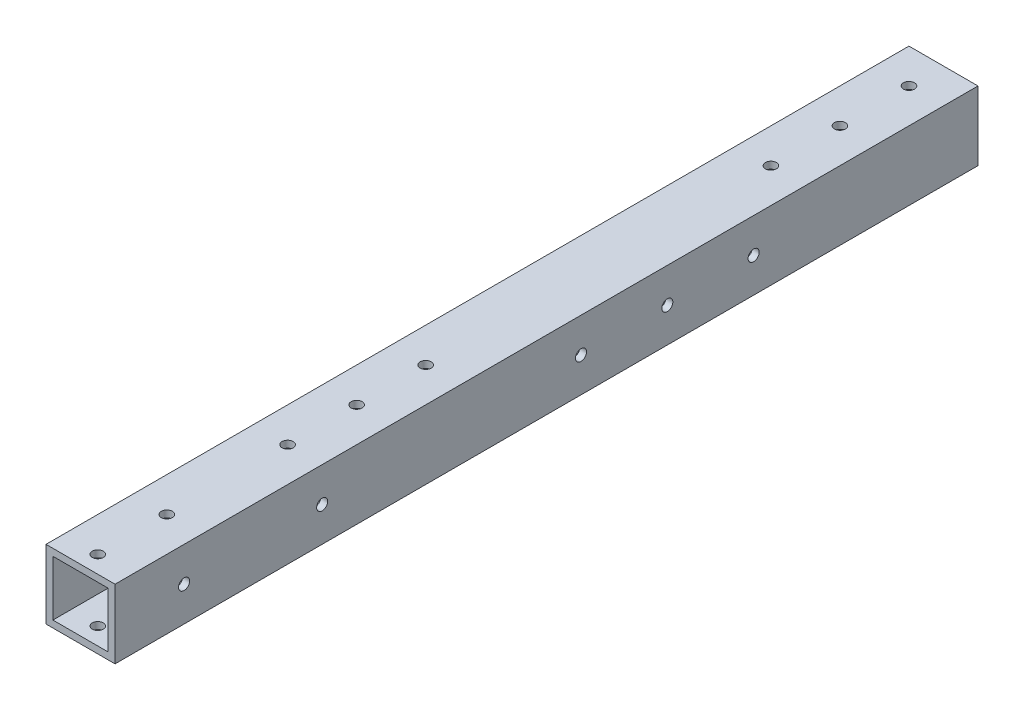
SolidWorks part; units mm, degrees
material "6061 合金"
ref_plane "前视基准面" through (0, 0, 0) normal (0, 0, 1) x (1, 0, 0)
ref_plane "上视基准面" through (0, 0, 0) normal (0, 1, 0) x (1, 0, 0)
ref_plane "右视基准面" through (0, 0, 0) normal (1, 0, 0) x (0, 0, -1)
other "Configuration Table"
sketch "草图1" plane through (0, 0, 0) normal (0, 0, 1) x (1, 0, 0)
  line L1 (0, 0) -> (20, 0)
  line L2 (0, 0) -> (0, 20)
  line L3 (0, 20) -> (20, 20)
  line L4 (20, 0) -> (20, 20)
  dimension "D1" = 20
  dimension "D2" = 20
extrude "拉伸-薄壁1" add sketch "草图1" along normal blind 250 thin thin type one direction reverse wall 2
sketch "草图2" plane through (0, 0, 0) normal (0, -1, 0) x (1, 0, 0)
  line L0 (10, 0) -> (10, 48.774) construction
  line L1 (0, 0) -> (20, 0) construction
  circle A0 centre (10, 10) radius 1.6
  circle A1 centre (10, 30) radius 1.6
  circle A2 centre (10, 50) radius 1.6
  dimension "D1" = 3.2
  dimension "D2" = 10
  dimension "D3" = 20
  dimension "D4" = 20
extrude "切除-拉伸1" cut sketch "草图2" against normal through all
sketch "草图3" plane through (0, 20, 0) normal (0, 1, 0) x (1, 0, 0)
  line L0 (10, -250) -> (10, -150) construction
  line L1 (20, -250) -> (0, -250) construction
  circle A0 centre (10, -150) radius 1.6
  circle A1 centre (10, -170) radius 1.6
  circle A2 centre (10, -190) radius 1.6
  circle A3 centre (10, -245) radius 1.6
  circle A4 centre (10, -225) radius 1.6
  dimension "D2" = 3.2
  dimension "D3" = 20
  dimension "D4" = 20
  dimension "D5" = 5
  dimension "D6" = 20
  dimension "D1" = 100
extrude "切除-拉伸2" cut sketch "草图3" against normal through all
sketch "草图4" plane through (20, 0, 0) normal (1, 0, 0) x (0, 0, -1)
  line L0 (-250, 10) -> (-230, 10) construction
  line L1 (-250, 0) -> (-250, 20) construction
  circle A0 centre (-230, 10) radius 1.6
  circle A1 centre (-190, 10) radius 1.6
  point P7 (0, 0)
  dimension "D1" = 3.2
  dimension "D3" = 40
  dimension "D2" = 20
extrude "切除-拉伸3" cut sketch "草图4" against normal through all
sketch "草图5" plane through (20, 0, 0) normal (1, 0, 0) x (0, 0, -1)
  line L0 (0, 10) -> (-114.4239, 10) construction
  line L1 (0, 0) -> (0, 20) construction
  circle A0 centre (-90, 10) radius 1.6
  circle A1 centre (-115, 10) radius 1.6
  circle A2 centre (-65, 10) radius 1.6
  dimension "D1" = 3.2
  dimension "D2" = 90
  dimension "D3" = 25
  dimension "D4" = 25
extrude "切除-拉伸4" cut sketch "草图5" against normal through all
